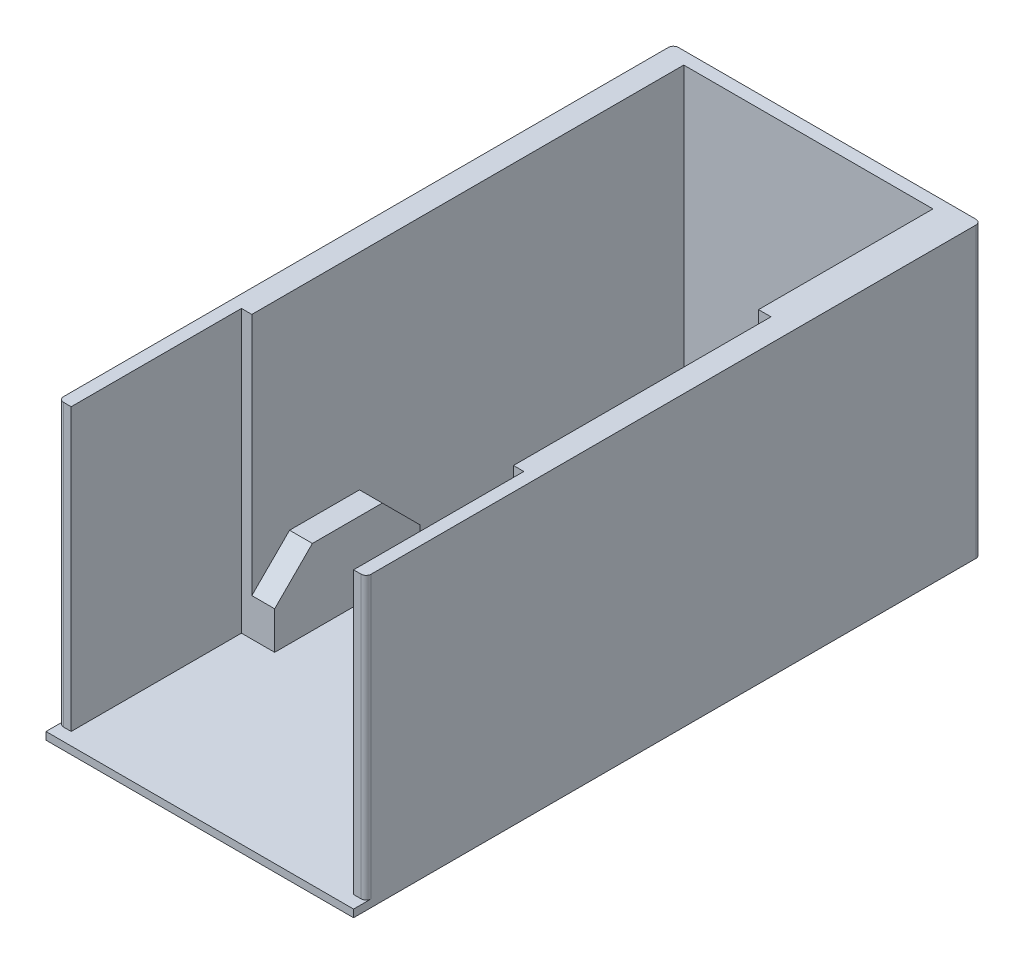
SolidWorks part; units mm, degrees
ref_plane "Front Plane" through (0, 0, 0) normal (0, 0, 1) x (1, 0, 0)
ref_plane "Top Plane" through (0, 0, 0) normal (0, 1, 0) x (1, 0, 0)
ref_plane "Right Plane" through (0, 0, 0) normal (1, 0, 0) x (0, 0, -1)
sketch "Sketch1" plane through (0, 0, 0) normal (0, 1, 0) x (1, 0, 0)
  line L0 (0, 0) -> (0, 2095.5) construction
  line L1 (-863.6, -520.7) -> (863.6, -520.7)
  line L2 (-863.6, -520.7) -> (-863.6, 520.7)
  line L3 (-863.6, 520.7) -> (863.6, 520.7)
  line L4 (863.6, -520.7) -> (863.6, 520.7)
  line L5 (-863.6, -520.7) -> (863.6, 520.7) construction
  line L6 (-863.6, 520.7) -> (863.6, -520.7) construction
  line L7 (-660.4, 520.7) -> (660.4, 520.7)
  line L8 (-660.4, 520.7) -> (-660.4, 1409.7)
  line L9 (-660.4, 1409.7) -> (660.4, 1409.7)
  line L10 (660.4, 520.7) -> (660.4, 1409.7)
  line L12 (-800.1, 1409.7) -> (800.1, 1409.7)
  line L13 (-800.1, 1409.7) -> (-800.1, 2095.5)
  line L14 (-800.1, 2095.5) -> (800.1, 2095.5)
  line L15 (800.1, 1409.7) -> (800.1, 2095.5)
  line L16 (-800.1, 2095.5) -> (723.9, 2095.5)
  line L17 (-800.1, 2095.5) -> (-800.1, 3162.3)
  line L18 (-800.1, 3162.3) -> (723.9, 3162.3)
  line L19 (723.9, 2095.5) -> (723.9, 3162.3)
  point P0 (0, 0)
  point P10 (0, 1409.7)
  point P13 (0, 2095.5)
  dimension "D1" = 1727.2
  dimension "D2" = 1041.4
  dimension "D3" = 1320.8
  dimension "D4" = 889
  dimension "D5" = 1600.2
  dimension "D6" = 685.8
  dimension "D7" = 1524
  dimension "D8" = 1066.8
sketch "Sketch2" plane through (0, 0, 0) normal (0, 1, 0) x (1, 0, 0)
  line L0 (-275, 3062.3) -> (-275, 3012.3) construction
  line L1 (-450, 3012.3) -> (-100, 3012.3)
  line L2 (-450, 3012.3) -> (-450, 2512.3)
  line L3 (-450, 2512.3) -> (-100, 2512.3)
  line L4 (-100, 3012.3) -> (-100, 2512.3)
  line L5 (-500, 3062.3) -> (-50, 3062.3)
  line L6 (-500, 3062.3) -> (-500, 2462.3)
  line L7 (-500, 2462.3) -> (-50, 2462.3)
  line L8 (-50, 3062.3) -> (-50, 2462.3)
  line L9 (-450, 2762.3) -> (-500, 2762.3) construction
  line L10 (100, 3012.3) -> (100, 2512.3)
  line L11 (100, 3012.3) -> (450, 3012.3)
  line L12 (450, 3012.3) -> (450, 2512.3)
  line L13 (100, 2512.3) -> (450, 2512.3)
  line L14 (50, 3062.3) -> (50, 2462.3)
  line L15 (50, 3062.3) -> (500, 3062.3)
  line L16 (500, 3062.3) -> (500, 2462.3)
  line L17 (50, 2462.3) -> (500, 2462.3)
  line L18 (100, 2312.3) -> (100, 1812.3)
  line L19 (100, 2312.3) -> (450, 2312.3)
  line L20 (450, 2312.3) -> (450, 1812.3)
  line L21 (100, 1812.3) -> (450, 1812.3)
  line L22 (50, 2362.3) -> (50, 1762.3)
  line L23 (50, 2362.3) -> (500, 2362.3)
  line L24 (500, 2362.3) -> (500, 1762.3)
  line L25 (50, 1762.3) -> (500, 1762.3)
  line L26 (100, 1612.3) -> (100, 1112.3)
  line L27 (100, 1612.3) -> (450, 1612.3)
  line L28 (450, 1612.3) -> (450, 1112.3)
  line L29 (100, 1112.3) -> (450, 1112.3)
  line L30 (50, 1662.3) -> (50, 1062.3)
  line L31 (50, 1662.3) -> (500, 1662.3)
  line L32 (500, 1662.3) -> (500, 1062.3)
  line L33 (50, 1062.3) -> (500, 1062.3)
  line L34 (100, 912.3) -> (100, 412.3)
  line L35 (100, 912.3) -> (450, 912.3)
  line L36 (450, 912.3) -> (450, 412.3)
  line L37 (100, 412.3) -> (450, 412.3)
  line L38 (50, 962.3) -> (50, 362.3)
  line L39 (50, 962.3) -> (500, 962.3)
  line L40 (500, 962.3) -> (500, 362.3)
  line L41 (50, 362.3) -> (500, 362.3)
  line L42 (-450, 2312.3) -> (-450, 1812.3)
  line L43 (-450, 2312.3) -> (-100, 2312.3)
  line L44 (-100, 2312.3) -> (-100, 1812.3)
  line L45 (-450, 1812.3) -> (-100, 1812.3)
  line L46 (-500, 2362.3) -> (-500, 1762.3)
  line L47 (-500, 2362.3) -> (-50, 2362.3)
  line L48 (-50, 2362.3) -> (-50, 1762.3)
  line L49 (-500, 1762.3) -> (-50, 1762.3)
  line L50 (-450, 1612.3) -> (-450, 1112.3)
  line L51 (-450, 1612.3) -> (-100, 1612.3)
  line L52 (-100, 1612.3) -> (-100, 1112.3)
  line L53 (-450, 1112.3) -> (-100, 1112.3)
  line L54 (-500, 1662.3) -> (-500, 1062.3)
  line L55 (-500, 1662.3) -> (-50, 1662.3)
  line L56 (-50, 1662.3) -> (-50, 1062.3)
  line L57 (-500, 1062.3) -> (-50, 1062.3)
  line L58 (-450, 912.3) -> (-450, 412.3)
  line L59 (-450, 912.3) -> (-100, 912.3)
  line L60 (-100, 912.3) -> (-100, 412.3)
  line L61 (-450, 412.3) -> (-100, 412.3)
  line L62 (-500, 962.3) -> (-500, 362.3)
  line L63 (-500, 962.3) -> (-50, 962.3)
  line L64 (-50, 962.3) -> (-50, 362.3)
  line L65 (-500, 362.3) -> (-50, 362.3)
  line L66 (-450, 3012.3) -> (100, 3012.3) construction
  line L67 (-450, 3012.3) -> (-450, 2312.3) construction
  line L68 (-50, 3062.3) -> (50, 3062.3) construction
  line L69 (0, 3062.3) -> (0, 2095.5) construction
  line L70 (-500, 2462.3) -> (-500, 2362.3)
  line L71 (-550, 3112.3) -> (550, 3112.3)
  line L72 (-550, 3112.3) -> (-550, 312.3)
  line L73 (-550, 312.3) -> (550, 312.3)
  line L74 (550, 3112.3) -> (550, 312.3)
  line L75 (-800.1, 3162.3) -> (723.9, 3162.3) construction
  dimension "D1" = 350
  dimension "D2" = 500
  dimension "D3" = 450
  dimension "D4" = 600
  dimension "D5" = 2
  dimension "D7" = 90
  dimension "D8" = 550
  dimension "D9" = 50
  dimension "D10" = 50
  dimension "D11" = 50
  dimension "D12" = 50
  dimension "D13" = 100
  dimension "D14" = 50
  dimension "D6" = 4
sketch "Resized Everything" plane through (0, 0, 0) normal (0, 1, 0) x (1, 0, 0)
  line L85 (-790.321, 2977.388) -> (-697.865, 2977.388)
  line L86 (-697.865, 2977.388) -> (-697.865, 3039.618)
  line L87 (-790.321, 3039.618) -> (-697.865, 3039.618)
  line L88 (-790.321, 2977.388) -> (-790.321, 3039.618)
  line L89 (-804.545, 2904.49) -> (-683.641, 2904.49)
  line L90 (-683.641, 2904.49) -> (-683.641, 2977.388)
  line L91 (-804.545, 2977.388) -> (-683.641, 2977.388)
  line L92 (-804.545, 2904.49) -> (-804.545, 2977.388)
  line L93 (-800.1, 3039.618) -> (-800.1, 3087.624)
  line L94 (-800.1, 3039.618) -> (-688.086, 3039.618)
  line L95 (-688.086, 3039.618) -> (-688.086, 3087.624)
  line L96 (-800.1, 3087.624) -> (-688.086, 3087.624)
  line L97 (-800.1, 3087.624) -> (-693.42, 3087.624)
  line L98 (-693.42, 3087.624) -> (-693.42, 3162.3)
  line L99 (-800.1, 3162.3) -> (-693.42, 3162.3)
  line L100 (-800.1, 3087.624) -> (-800.1, 3162.3)
  line L101 (-779.093, 3113.3) -> (-779.093, 3106.3)
  line L102 (-779.093, 3113.3) -> (-747.593, 3113.3)
  line L103 (-747.593, 3155.3) -> (-747.593, 3113.3)
  line L104 (-779.093, 3155.3) -> (-747.593, 3155.3)
  line L105 (-779.093, 3155.3) -> (-779.093, 3113.3)
  line L106 (-775.593, 3151.8) -> (-751.093, 3151.8)
  line L107 (-751.093, 3151.8) -> (-751.093, 3116.8)
  line L108 (-775.593, 3116.8) -> (-751.093, 3116.8)
  line L109 (-775.593, 3151.8) -> (-775.593, 3116.8)
  line L110 (-740.593, 3106.3) -> (-740.593, 3064.3)
  line L111 (-740.593, 3064.3) -> (-709.093, 3064.3)
  line L112 (-709.093, 3106.3) -> (-709.093, 3064.3)
  line L113 (-740.593, 3106.3) -> (-709.093, 3106.3)
  line L114 (-737.093, 3102.8) -> (-737.093, 3067.8)
  line L115 (-737.093, 3067.8) -> (-712.593, 3067.8)
  line L116 (-712.593, 3102.8) -> (-712.593, 3067.8)
  line L117 (-737.093, 3102.8) -> (-712.593, 3102.8)
  line L118 (-740.593, 3155.3) -> (-740.593, 3113.3)
  line L119 (-740.593, 3113.3) -> (-709.093, 3113.3)
  line L120 (-709.093, 3155.3) -> (-709.093, 3113.3)
  line L121 (-740.593, 3155.3) -> (-709.093, 3155.3)
  line L122 (-737.093, 3151.8) -> (-737.093, 3116.8)
  line L123 (-737.093, 3151.8) -> (-712.593, 3151.8)
  line L124 (-712.593, 3151.8) -> (-712.593, 3116.8)
  line L125 (-737.093, 3116.8) -> (-712.593, 3116.8)
  line L126 (-740.593, 3008.3) -> (-740.593, 2966.3)
  line L127 (-740.593, 2966.3) -> (-709.093, 2966.3)
  line L128 (-709.093, 3008.3) -> (-709.093, 2966.3)
  line L129 (-740.593, 3008.3) -> (-709.093, 3008.3)
  line L130 (-737.093, 3004.8) -> (-737.093, 2969.8)
  line L131 (-737.093, 2969.8) -> (-712.593, 2969.8)
  line L132 (-712.593, 3004.8) -> (-712.593, 2969.8)
  line L133 (-737.093, 3004.8) -> (-712.593, 3004.8)
  line L134 (-740.593, 3057.3) -> (-740.593, 3015.3)
  line L135 (-740.593, 3015.3) -> (-709.093, 3015.3)
  line L136 (-709.093, 3057.3) -> (-709.093, 3015.3)
  line L137 (-740.593, 3057.3) -> (-709.093, 3057.3)
  line L138 (-737.093, 3053.8) -> (-737.093, 3018.8)
  line L139 (-737.093, 3053.8) -> (-712.593, 3053.8)
  line L140 (-712.593, 3053.8) -> (-712.593, 3018.8)
  line L141 (-737.093, 3018.8) -> (-712.593, 3018.8)
  line L142 (-779.093, 3057.3) -> (-779.093, 3015.3)
  line L143 (-779.093, 3015.3) -> (-747.593, 3015.3)
  line L144 (-747.593, 3057.3) -> (-747.593, 3015.3)
  line L145 (-779.093, 3057.3) -> (-747.593, 3057.3)
  line L146 (-775.593, 3053.8) -> (-775.593, 3018.8)
  line L147 (-775.593, 3018.8) -> (-751.093, 3018.8)
  line L148 (-751.093, 3053.8) -> (-751.093, 3018.8)
  line L149 (-775.593, 3053.8) -> (-751.093, 3053.8)
  line L150 (-779.093, 3106.3) -> (-779.093, 3064.3)
  line L151 (-779.093, 3064.3) -> (-747.593, 3064.3)
  line L152 (-747.593, 3106.3) -> (-747.593, 3064.3)
  line L153 (-779.093, 3106.3) -> (-747.593, 3106.3)
  line L154 (-775.593, 3102.8) -> (-775.593, 3067.8)
  line L155 (-775.593, 3102.8) -> (-751.093, 3102.8)
  line L156 (-751.093, 3102.8) -> (-751.093, 3067.8)
  line L157 (-775.593, 3067.8) -> (-751.093, 3067.8)
  line L158 (-782.593, 3158.8) -> (-705.593, 3158.8)
  line L159 (-705.593, 3158.8) -> (-705.593, 2962.8)
  line L160 (-782.593, 2962.8) -> (-705.593, 2962.8)
  line L161 (-782.593, 3158.8) -> (-782.593, 2962.8)
  line L162 (-779.093, 3008.3) -> (-779.093, 2966.3)
  line L163 (-779.093, 2966.3) -> (-747.593, 2966.3)
  line L164 (-747.593, 3008.3) -> (-747.593, 2966.3)
  line L165 (-779.093, 3008.3) -> (-747.593, 3008.3)
  line L166 (-775.593, 3004.8) -> (-775.593, 2969.8)
  line L167 (-775.593, 3004.8) -> (-751.093, 3004.8)
  line L168 (-751.093, 3004.8) -> (-751.093, 2969.8)
  line L169 (-775.593, 2969.8) -> (-751.093, 2969.8)
sketch "Sketch6" plane through (0, 0, 0) normal (0, 1, 0) x (1, 0, 0)
  line L0 (-800.1, 3162.3) -> (723.9, 3162.3) construction
  line L1 (-748.0935, 2917.905) -> (-748.0935, 3167.3) construction
  line L2 (-809.2275, 2917.905) -> (-686.9595, 2917.905)
  line L3 (-686.9595, 2917.905) -> (-686.9595, 3167.3)
  line L4 (-686.9595, 3167.3) -> (-809.2275, 3167.3)
  line L5 (-696.087, 3048.381) -> (-696.087, 2990.596)
  line L6 (-800.1, 3048.381) -> (-800.1, 2990.596)
  line L7 (-809.2275, 2917.905) -> (-809.2275, 3167.3)
  line L8 (-701.04, 3162.3) -> (-696.087, 3162.3)
  line L9 (-696.087, 3162.3) -> (-696.087, 3092.958)
  line L10 (-804.2275, 2922.905) -> (-809.2275, 2922.905)
  line L11 (-691.9595, 2922.905) -> (-686.9595, 2922.905)
  line L16 (-791.0195, 2990.596) -> (-705.1675, 2990.596)
  line L17 (-705.1675, 2990.596) -> (-705.1675, 3048.381)
  line L18 (-791.0195, 3048.381) -> (-705.1675, 3048.381)
  line L19 (-791.0195, 2990.596) -> (-791.0195, 3048.381)
  line L20 (-804.2275, 2922.905) -> (-691.9595, 2922.905)
  line L21 (-691.9595, 2922.905) -> (-691.9595, 2990.596)
  line L22 (-804.2275, 2990.596) -> (-691.9595, 2990.596)
  line L23 (-804.2275, 2922.905) -> (-804.2275, 2990.596)
  line L24 (-800.1, 3048.381) -> (-800.1, 3092.958)
  line L25 (-800.1, 3048.381) -> (-696.087, 3048.381)
  line L26 (-696.087, 3048.381) -> (-696.087, 3092.958)
  line L27 (-800.1, 3092.958) -> (-696.087, 3092.958)
  line L28 (-800.1, 3092.958) -> (-701.04, 3092.958)
  line L29 (-701.04, 3092.958) -> (-701.04, 3162.3)
  line L30 (-800.1, 3162.3) -> (-701.04, 3162.3)
  line L31 (-800.1, 3092.958) -> (-800.1, 3162.3)
  point P3 (-748.0935, 2922.905)
  dimension "D1" = 239.395
  dimension "D2" = 5
  dimension "D3" = 5
  dimension "D4" = 5
extrude "Boss-Extrude1" add sketch "Sketch6" along normal blind 111.8 contours L2 L1 L20 L23 L22 L6 L24 L31 L30 L4 L7 | L1 L2 L3 L4 L30 L29 L27 L26 L5 L22 L21 L20 | L29 L27 L9 L8
sketch "Sketch7" plane through (0, 0, 0) normal (0, -1, 0) x (1, 0, 0)
  line L0 (-800.1, -3048.381) -> (-800.1, -2990.596) construction
  line L1 (-696.087, -3048.381) -> (-696.087, -2990.596) construction
  line L2 (-800.1, -3048.381) -> (-800.1, -3092.958) construction
  line L3 (-800.1, -3092.958) -> (-696.087, -3092.958) construction
  line L4 (-800.1, -3092.958) -> (-701.04, -3092.958) construction
  line L5 (-701.04, -3092.958) -> (-701.04, -3162.3) construction
  line L6 (-800.1, -3162.3) -> (-701.04, -3162.3) construction
  line L7 (-800.1, -3092.958) -> (-800.1, -3162.3) construction
  line L8 (-701.04, -3162.3) -> (-696.087, -3162.3) construction
  line L9 (-696.087, -3162.3) -> (-696.087, -3092.958) construction
  line L10 (-696.087, -3048.381) -> (-696.087, -3092.958) construction
  line L11 (-800.1, -3048.381) -> (-696.087, -3048.381) construction
  line L12 (-809.2275, -2917.905) -> (-686.9595, -2917.905) construction
  line L13 (-686.9595, -2917.905) -> (-686.9595, -3167.3) construction
  line L14 (-686.9595, -3167.3) -> (-809.2275, -3167.3) construction
  line L15 (-809.2275, -2917.905) -> (-809.2275, -3167.3) construction
  line L16 (-804.2275, -2922.905) -> (-691.9595, -2922.905) construction
  line L17 (-691.9595, -2922.905) -> (-691.9595, -2990.596) construction
  line L18 (-804.2275, -2990.596) -> (-691.9595, -2990.596) construction
  line L19 (-804.2275, -2922.905) -> (-804.2275, -2990.596) construction
  line L20 (-705.1675, -2990.596) -> (-705.1675, -3048.381) construction
  line L21 (-791.0195, -3048.381) -> (-705.1675, -3048.381) construction
  line L22 (-791.0195, -2990.596) -> (-791.0195, -3048.381) construction
  line L23 (-791.0195, -2990.596) -> (-705.1675, -2990.596) construction
  line L24 (-800.1, -3048.381) -> (-800.1, -2990.596)
  line L25 (-696.087, -3048.381) -> (-696.087, -2990.596)
  line L26 (-800.1, -3048.381) -> (-800.1, -3092.958)
  line L27 (-800.1, -3092.958) -> (-696.087, -3092.958)
  line L28 (-800.1, -3092.958) -> (-701.04, -3092.958)
  line L29 (-701.04, -3092.958) -> (-701.04, -3162.3)
  line L30 (-800.1, -3162.3) -> (-701.04, -3162.3)
  line L31 (-800.1, -3092.958) -> (-800.1, -3162.3)
  line L32 (-701.04, -3162.3) -> (-696.087, -3162.3)
  line L33 (-696.087, -3162.3) -> (-696.087, -3092.958)
  line L34 (-696.087, -3048.381) -> (-696.087, -3092.958)
  line L35 (-800.1, -3048.381) -> (-696.087, -3048.381)
  line L36 (-809.2275, -2917.905) -> (-686.9595, -2917.905)
  line L37 (-686.9595, -2917.905) -> (-686.9595, -3167.3)
  line L38 (-686.9595, -3167.3) -> (-809.2275, -3167.3)
  line L39 (-809.2275, -2917.905) -> (-809.2275, -3167.3)
  line L40 (-804.2275, -2922.905) -> (-691.9595, -2922.905)
  line L41 (-691.9595, -2922.905) -> (-691.9595, -2990.596)
  line L42 (-804.2275, -2990.596) -> (-691.9595, -2990.596)
  line L43 (-804.2275, -2922.905) -> (-804.2275, -2990.596)
  line L44 (-705.1675, -2990.596) -> (-705.1675, -3048.381)
  line L45 (-791.0195, -3048.381) -> (-705.1675, -3048.381)
  line L46 (-791.0195, -2990.596) -> (-791.0195, -3048.381)
  line L47 (-791.0195, -2990.596) -> (-705.1675, -2990.596)
extrude "Boss-Extrude2" add sketch "Sketch7" along normal blind 3 contours L39 L38 L37 L36
sketch "Sketch8" plane through (0, 0, 0) normal (0, 1, 0) x (1, 0, 0)
  line L0 (-691.9595, 2922.905) -> (-686.9595, 2922.905) construction
  line L1 (-804.2275, 2922.905) -> (-809.2275, 2922.905) construction
  line L2 (-800.1, 3048.381) -> (-800.1, 2990.596) construction
  line L3 (-696.087, 3048.381) -> (-696.087, 2990.596) construction
  line L4 (-800.1, 3048.381) -> (-800.1, 3092.958) construction
  line L5 (-800.1, 3092.958) -> (-696.087, 3092.958) construction
  line L6 (-800.1, 3092.958) -> (-701.04, 3092.958) construction
  line L7 (-701.04, 3092.958) -> (-701.04, 3162.3) construction
  line L8 (-800.1, 3162.3) -> (-701.04, 3162.3) construction
  line L9 (-800.1, 3092.958) -> (-800.1, 3162.3) construction
  line L10 (-804.2275, 2922.905) -> (-691.9595, 2922.905) construction
  line L11 (-691.9595, 2922.905) -> (-691.9595, 2990.596) construction
  line L12 (-804.2275, 2990.596) -> (-691.9595, 2990.596) construction
  line L13 (-804.2275, 2922.905) -> (-804.2275, 2990.596) construction
  line L14 (-701.04, 3162.3) -> (-696.087, 3162.3) construction
  line L15 (-696.087, 3162.3) -> (-696.087, 3092.958) construction
  line L16 (-696.087, 3048.381) -> (-696.087, 3092.958) construction
  line L17 (-800.1, 3048.381) -> (-696.087, 3048.381) construction
  line L18 (-809.2275, 2917.905) -> (-686.9595, 2917.905) construction
  line L19 (-686.9595, 2917.905) -> (-686.9595, 3167.3) construction
  line L20 (-686.9595, 3167.3) -> (-809.2275, 3167.3) construction
  line L21 (-809.2275, 2917.905) -> (-809.2275, 3167.3) construction
  line L22 (-705.1675, 2990.596) -> (-705.1675, 3048.381) construction
  line L23 (-791.0195, 3048.381) -> (-705.1675, 3048.381) construction
  line L24 (-791.0195, 2990.596) -> (-791.0195, 3048.381) construction
  line L25 (-791.0195, 2990.596) -> (-705.1675, 2990.596) construction
  line L26 (-691.9595, 2922.905) -> (-686.9595, 2922.905)
  line L27 (-804.2275, 2922.905) -> (-809.2275, 2922.905)
  line L28 (-800.1, 3048.381) -> (-800.1, 2990.596)
  line L29 (-696.087, 3048.381) -> (-696.087, 2990.596)
  line L30 (-800.1, 3048.381) -> (-800.1, 3092.958)
  line L31 (-800.1, 3092.958) -> (-696.087, 3092.958)
  line L32 (-800.1, 3092.958) -> (-701.04, 3092.958)
  line L33 (-701.04, 3092.958) -> (-701.04, 3162.3)
  line L34 (-800.1, 3162.3) -> (-701.04, 3162.3)
  line L35 (-800.1, 3092.958) -> (-800.1, 3162.3)
  line L36 (-804.2275, 2922.905) -> (-691.9595, 2922.905)
  line L37 (-691.9595, 2922.905) -> (-691.9595, 2990.596)
  line L38 (-804.2275, 2990.596) -> (-691.9595, 2990.596)
  line L39 (-804.2275, 2922.905) -> (-804.2275, 2990.596)
  line L40 (-701.04, 3162.3) -> (-696.087, 3162.3)
  line L41 (-696.087, 3162.3) -> (-696.087, 3092.958)
  line L42 (-696.087, 3048.381) -> (-696.087, 3092.958)
  line L43 (-800.1, 3048.381) -> (-696.087, 3048.381)
  line L44 (-809.2275, 2917.905) -> (-686.9595, 2917.905)
  line L45 (-686.9595, 2917.905) -> (-686.9595, 3167.3)
  line L46 (-686.9595, 3167.3) -> (-809.2275, 3167.3)
  line L47 (-809.2275, 2917.905) -> (-809.2275, 3167.3)
  line L48 (-705.1675, 2990.596) -> (-705.1675, 3048.381)
  line L49 (-791.0195, 3048.381) -> (-705.1675, 3048.381)
  line L50 (-791.0195, 2990.596) -> (-791.0195, 3048.381)
  line L51 (-791.0195, 2990.596) -> (-705.1675, 2990.596)
  line M17 (-696.087, 2990.596) -> (-696.087, 3092.958)
  line M21 (-800.1, 3162.3) -> (-800.1, 2990.596)
extrude "Boss-Extrude3" add sketch "Sketch8" along normal blind 30 contours L38 L50 L43 M21 | L48 L38 L43 M17
ref_plane "Plane1" through (-748.0935, 0, 0) normal (1, 0, 0) x (0, 0, -1)
sketch "Sketch9" plane through (-791.0195, 0, 0) normal (1, 0, 0) x (0, 0, -1)
  line L0 (2990.596, 15) -> (3005.596, 30)
  line L1 (3019.4885, 30) -> (3019.4885, 0) construction
  line L2 (3048.381, 15) -> (3033.381, 30)
  line L4 (2990.596, 0) -> (3048.381, 0)
  line L5 (3048.381, 0) -> (3048.381, 30)
  line L6 (3048.381, 30) -> (2990.596, 30)
  line L7 (2990.596, 30) -> (2990.596, 0)
  line L8 (2990.596, 0) -> (3048.381, 0)
  line L9 (3048.381, 0) -> (3048.381, 30)
  line L10 (3048.381, 30) -> (2990.596, 30)
  line L11 (2990.596, 30) -> (2990.596, 0)
  line M8 (3048.381, 0) -> (3048.381, 30)
  line M9 (3048.381, 30) -> (2990.596, 30)
  line M10 (2990.596, 30) -> (2990.596, 0)
  dimension "D2" = 45
  dimension "D1" = 0
extrude "Cut-Extrude1" cut sketch "Sketch9" against normal up to surface (9.0805 mm away) contours L0 M10 M9 | L2 M8 M9 up to face at (-800.1, 47.2667, -3067.0923)
sketch "Sketch10" plane through (-705.1675, 0, 0) normal (-1, 0, 0) x (0, 0, 1)
  line L0 (-3048.381, 15) -> (-3033.381, 30) construction
  line L1 (-2990.596, 15) -> (-3005.596, 30) construction
  line L2 (-3048.381, 15) -> (-3033.381, 30)
  line L3 (-2990.596, 15) -> (-3005.596, 30)
  line L4 (-3048.381, 0) -> (-2990.596, 0)
  line L5 (-3048.381, 30) -> (-3048.381, 0)
  line L6 (-2990.596, 30) -> (-3048.381, 30)
  line L7 (-2990.596, 0) -> (-2990.596, 30)
  line L8 (-3048.381, 0) -> (-2990.596, 0)
  line L9 (-3048.381, 30) -> (-3048.381, 0)
  line L10 (-2990.596, 30) -> (-3048.381, 30)
  line L11 (-2990.596, 0) -> (-2990.596, 30)
  line M6 (-2990.596, 0) -> (-2990.596, 30)
  line M7 (-2990.596, 30) -> (-3048.381, 30)
  line M8 (-3048.381, 30) -> (-3048.381, 0)
  dimension "D1" = 0
extrude "Cut-Extrude2" cut sketch "Sketch10" against normal up to surface (9.0805 mm away) contours L2 M8 M7 | L3 M6 M7 up to face at (-696.087, 47.2667, -3043.9783)
fillet "Fillet1" radius 2 4 edges at (-686.9595, 55.9, -2922.905) (-686.9595, 54.4, -3167.3) (-809.2275, 54.4, -3167.3) (-809.2275, 55.9, -2922.905)
equation "\"alpha\"= 1"
equation "\"bin_width\"= 0.5"
equation "\"bin_depth\"= 0.35"
equation "\"bin_height\"= 0.35"
